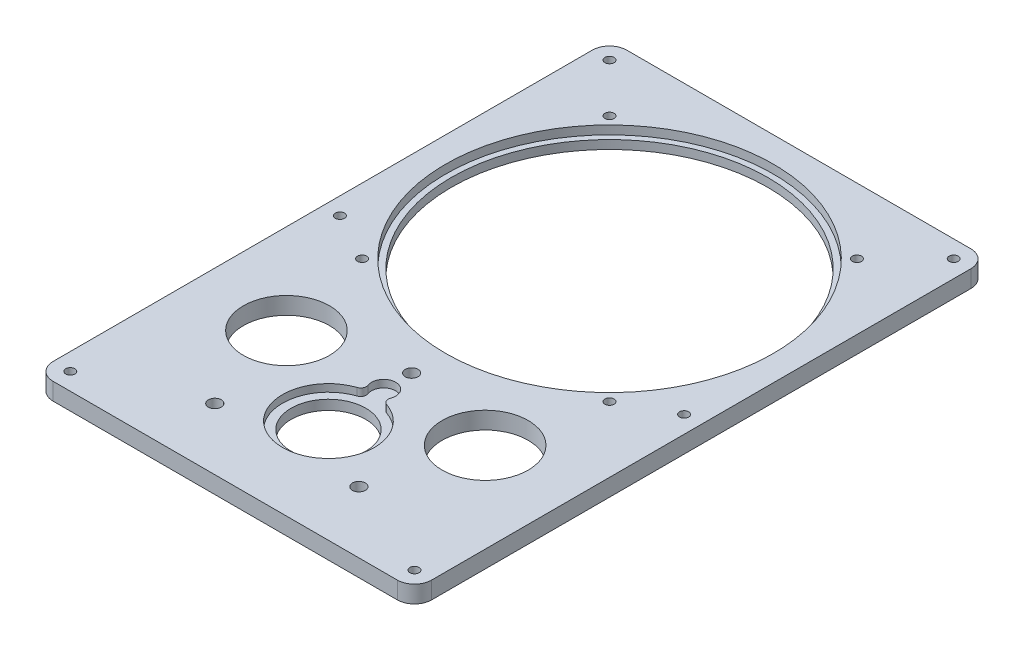
SolidWorks part; units mm, degrees
material "A-玻璃纤维"
ref_plane "前视基准面" through (0, 0, 0) normal (0, 0, 1) x (1, 0, 0)
ref_plane "上视基准面" through (0, 0, 0) normal (0, 1, 0) x (1, 0, 0)
ref_plane "右视基准面" through (0, 0, 0) normal (1, 0, 0) x (0, 0, -1)
sketch "草图2" plane through (0, 0, 0) normal (0, 1, 0) x (1, 0, 0)
  line L1 (-66, 100) -> (66, 100)
  line L2 (-66, 100) -> (-66, -100)
  line L3 (-66, -100) -> (66, -100)
  line L4 (66, 100) -> (66, -100)
  line L5 (0, -100) -> (0, 100) construction
  line L6 (-66, 0) -> (66, 0) construction
  point P0 (0, 0)
  dimension "D1" = 132
  dimension "D2" = 200
extrude "凸台-拉伸1" add sketch "草图2" along normal blind 6
sketch "草图3" plane through (0, 6, 0) normal (0, 1, 0) x (1, 0, 0)
  line L0 (-66, 0) -> (66, 0) construction
  line L1 (-66, 100) -> (-66, -100) construction
  line L2 (66, -100) -> (66, 100) construction
  line L3 (0, 100) -> (0, -100) construction
  line L4 (66, 100) -> (-66, 100) construction
  line L5 (-66, -100) -> (66, -100) construction
  circle A0 centre (0, 34) radius 57.15
  dimension "D1" = 114.3
  dimension "D2" = 34
extrude "切除-拉伸1" cut sketch "草图3" against normal blind 6
sketch "草图6" plane through (0, 0, 0) normal (0, 1, 0) x (1, 0, 0)
  line L0 (-66, 0) -> (66, 0) construction
  line L1 (-66, 100) -> (-66, -100) construction
  line L2 (66, -100) -> (66, 100) construction
  line L3 (0, 100) -> (0, -100) construction
  line L4 (66, 100) -> (-66, 100) construction
  line L5 (-66, -100) -> (66, -100) construction
  line L6 (-57.15, 34) -> (57.15, 34) construction
  circle A0 centre (0, 34) radius 57.15 construction
  circle A1 centre (0, 34) radius 57.15
  circle A2 centre (0, 34) radius 55.15
  dimension "D1" = 110.3
  dimension "D2" = 114.3
extrude "凸台-拉伸2" add sketch "草图6" along normal blind 3
sketch "草图10" plane through (0, 6, 0) normal (0, 1, 0) x (1, 0, 0)
  line L0 (-57.15, 34) -> (57.15, 34) construction
  line L1 (0, 100) -> (0, -100) construction
  line L2 (66, 100) -> (-66, 100) construction
  line L3 (-66, -100) -> (66, -100) construction
  line L4 (0, 34) -> (43.1335, -9.1335) construction
  circle A0 centre (0, 34) radius 57.15 construction
  circle A1 centre (0, 34) radius 57.15 construction
  circle A2 centre (0, 34) radius 61 construction
  circle A3 centre (43.1335, -9.1335) radius 1.6
  circle A4 centre (-43.1335, -9.1335) radius 1.6
  circle A5 centre (-43.1335, 77.1335) radius 1.6
  circle A6 centre (43.1335, 77.1335) radius 1.6
  point P18 (0, 34)
  point P23 (0, 34)
  point P26 (0, 34)
  point P29 (0, 34)
  dimension "D1" = 122
  dimension "D3" = 3.2
  dimension "D2" = 45
  dimension "D4" = 4
extrude "切除-拉伸2" cut sketch "草图10" against normal blind 6
sketch "草图11" plane through (0, 6, 0) normal (0, 1, 0) x (1, 0, 0)
  line L0 (0, 100) -> (0, -100) construction
  line L1 (66, 100) -> (-66, 100) construction
  line L2 (-66, -100) -> (66, -100) construction
  line L3 (-55.15, 34) -> (55.15, 34) construction
  line L4 (66, 0) -> (-66, 0) construction
  line L5 (66, -100) -> (66, 100) construction
  line L6 (-66, 100) -> (-66, -100) construction
  circle A0 centre (0, -64) radius 13
  circle A1 centre (0, 34) radius 55.15 construction
  dimension "D1" = 26
  dimension "D2" = 64
extrude "切除-拉伸3" cut sketch "草图11" against normal blind 6
sketch "草图12" plane through (0, 6, 0) normal (0, 1, 0) x (1, 0, 0)
  circle A0 centre (0, -64) radius 16
  dimension "D1" = 32
extrude "切除-拉伸4" cut sketch "草图12" against normal blind 2.6
sketch "草图13" plane through (0, 6, 0) normal (0, 1, 0) x (1, 0, 0)
  line L0 (0, 100) -> (0, -100) construction
  line L1 (66, 100) -> (-66, 100) construction
  line L2 (-66, -100) -> (66, -100) construction
  line L3 (-16, -64) -> (16, -64) construction
  circle A0 centre (0, -44.75) radius 4.2
  circle A1 centre (0, -64) radius 16 construction
  circle A2 centre (0, -64) radius 16 construction
  dimension "D1" = 8.4
  dimension "D2" = 19.25
extrude "切除-拉伸5" cut sketch "草图13" against normal blind 2.6
fillet "圆角1" radius 2 2 edges at (-2.4184, 4.7, 48.1838) (2.4184, 4.7, 48.1838)
sketch "草图14" plane through (0, 6, 0) normal (0, 1, 0) x (1, 0, 0)
  line L0 (0, 100) -> (0, -100) construction
  line L1 (66, 100) -> (-66, 100) construction
  line L2 (-66, -100) -> (66, -100) construction
  circle A0 centre (0, -64) radius 29 construction
  circle A1 centre (0, -35) radius 2.25
  circle A2 centre (25.1147, -78.5) radius 2.25
  circle A3 centre (-25.1147, -78.5) radius 2.25
  dimension "D1" = 58
  dimension "D2" = 4.5
  dimension "D3" = 3
extrude "切除-拉伸6" cut sketch "草图14" against normal blind 6
fillet "圆角2" radius 6 4 edges at (-66, 3, 100) (66, 3, 100) (66, 3, -100) (-66, 3, -100)
sketch "草图15" plane through (0, 6, 0) normal (0, 1, 0) x (1, 0, 0)
  line L0 (0, 100) -> (0, -100) construction
  line L1 (60, 100) -> (-60, 100) construction
  line L2 (-60, -100) -> (60, -100) construction
  line L3 (66, 0) -> (-66, 0) construction
  line L4 (66, -94) -> (66, 94) construction
  line L5 (-66, 94) -> (-66, -94) construction
  line L6 (60, 94) -> (60, -94) construction
  circle A0 centre (60, 94) radius 1.6
  circle A1 centre (-60, 94) radius 1.6
  circle A2 centre (60, -94) radius 1.6
  circle A3 centre (-60, -94) radius 1.6
  circle A4 centre (60, 0) radius 1.6
  circle A5 centre (-60, 0) radius 1.6
  dimension "D1" = 3.2
  dimension "D2" = 3.2
extrude "切除-拉伸7" cut sketch "草图15" against normal blind 6
sketch "草图17" plane through (0, 6, 0) normal (0, 1, 0) x (1, 0, 0)
  line L0 (0, 100) -> (0, -100) construction
  line L1 (60, 100) -> (-60, 100) construction
  line L2 (-60, -100) -> (60, -100) construction
  line L4 (25.1147, -78.5) -> (-65.4244, -26.2272) construction
  circle A0 centre (34.641, -44) radius 15
  circle A1 centre (-34.641, -44) radius 15
  circle A2 centre (0, -64) radius 13 construction
  point P11 (0, -64)
  dimension "D1" = 40
  dimension "D2" = 30
extrude "切除-拉伸9" cut sketch "草图17" against normal blind 6
sketch "草图18" plane through (0, 0, 0) normal (0, 1, 0) x (1, 0, 0)
  line L0 (0, 173.1421) -> (0, -165.8159) construction
  line L1 (-160.4434, 0) -> (211.2382, 0) construction
  line L2 (-57.15, 34) -> (57.15, 34) construction
  circle A0 centre (0, 34) radius 57.15 construction
